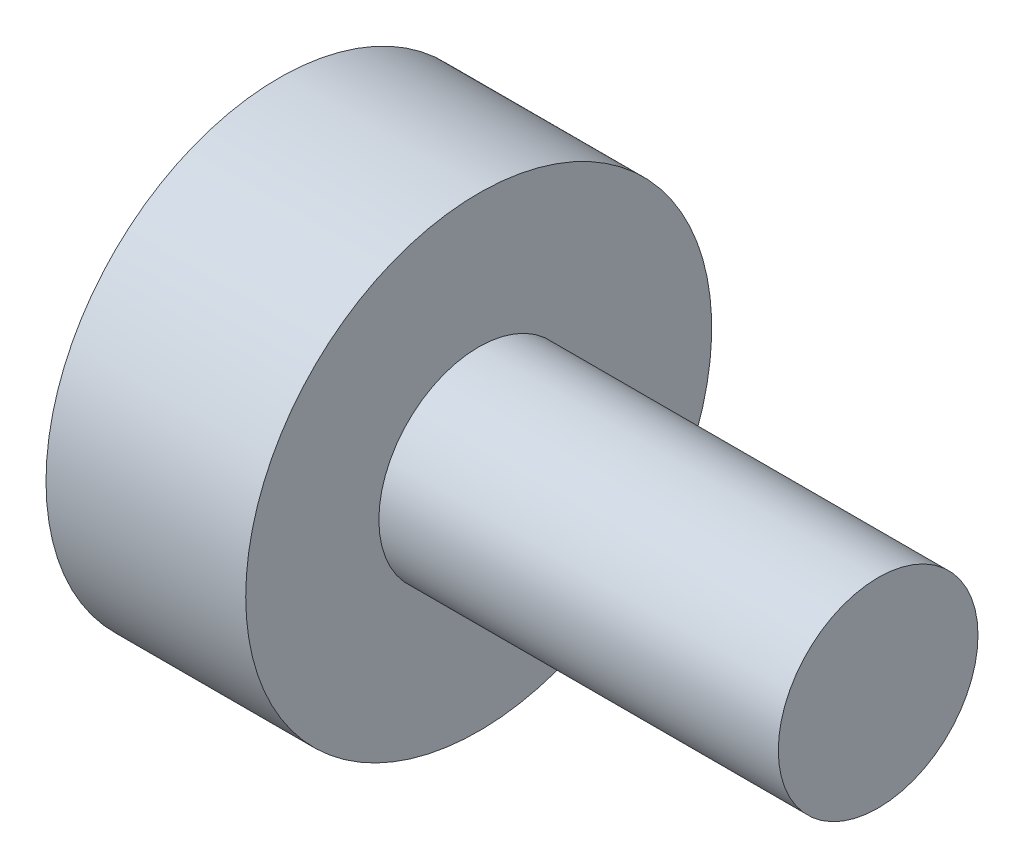
SolidWorks part; units mm, degrees
ref_plane "Спереди" through (0, 0, 0) normal (0, 0, 1) x (1, 0, 0)
ref_plane "Сверху" through (0, 0, 0) normal (0, 1, 0) x (1, 0, 0)
ref_plane "Справа" through (0, 0, 0) normal (1, 0, 0) x (0, 0, -1)
sketch "Эскиз1" plane through (0, 0, 0) normal (0, 0, 1) x (1, 0, 0)
  line L0 (0, 0) -> (100, 0)
  line L1 (0, 0) -> (0, 20)
  line L2 (0, 20) -> (10, 20)
  line L3 (10, 20) -> (10, 35)
  line L4 (10, 35) -> (40, 35)
  line L5 (40, 35) -> (40, 15)
  line L6 (40, 15) -> (100, 15)
  line L7 (100, 0) -> (100, 15)
revolve "Повернуть1" add sketch "Эскиз1" angle 360 about L0
sketch "Эскиз2" plane through (0, 0, 0) normal (1, 0, 0) x (0, 0, -1)
  circle A0 centre (10, 10) radius 5
extrude "Вырез-Вытянуть1" cut sketch "Эскиз2" along normal blind 20
sketch "Эскиз3" plane through (0, 0, 0) normal (1, 0, 0) x (0, 0, -1)
  circle A0 centre (-10, 10) radius 5
extrude "Вырез-Вытянуть2" cut sketch "Эскиз3" along normal blind 20
